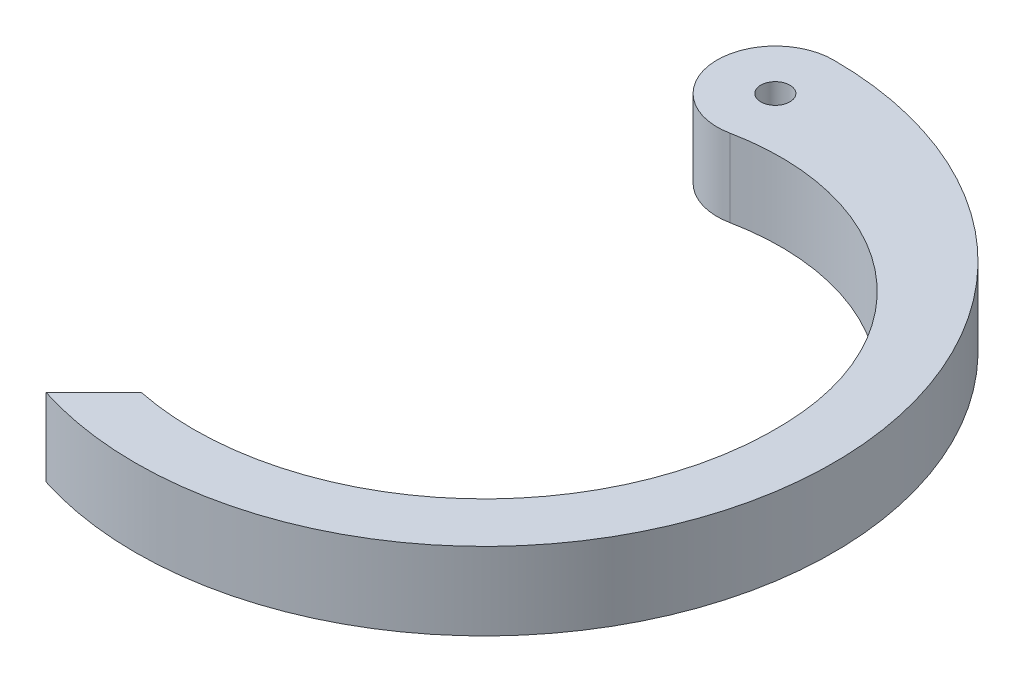
SolidWorks part; units mm, degrees
ref_plane "Front Plane" through (0, 0, 0) normal (0, 0, 1) x (1, 0, 0)
ref_plane "Top Plane" through (0, 0, 0) normal (0, 1, 0) x (1, 0, 0)
ref_plane "Right Plane" through (0, 0, 0) normal (1, 0, 0) x (0, 0, -1)
sketch "Sketch1" plane through (0, 0, 0) normal (0, 1, 0) x (1, 0, 0)
  line L0 (-17.3234, -102.0862) -> (-9.525, -94.2878)
  line L1 (0, -95.25) -> (0, -104.775)
  circle A0 centre (0, 0) radius 2.3813
  arc A1 (0, 9.525) -> (1.8955, -9.3345) centre (0, 0) ccw
  arc A2 (-17.3234, -102.0862) -> (0, 9.525) centre (0, -47.625) ccw
  arc A3 (-9.525, -94.2878) -> (47.3863, -42.8625) centre (0, -47.625) ccw
  arc A4 (2.3805, -0.0595) -> (-9.4773, -0.9525) centre (0, -47.625) ccw
  arc A5 (1.8955, -9.3345) -> (47.3863, -42.8625) centre (9.4773, -46.6725) cw
  dimension "D1" = 4.7625
  dimension "D2" = 19.05
  dimension "D3" = 114.3
  dimension "D4" = 9.525
  dimension "D7" = 38.1
  dimension "D5" = 45
  dimension "D6" = 9.525
extrude "Boss-Extrude1" add sketch "Sketch1" along normal blind 12.7
